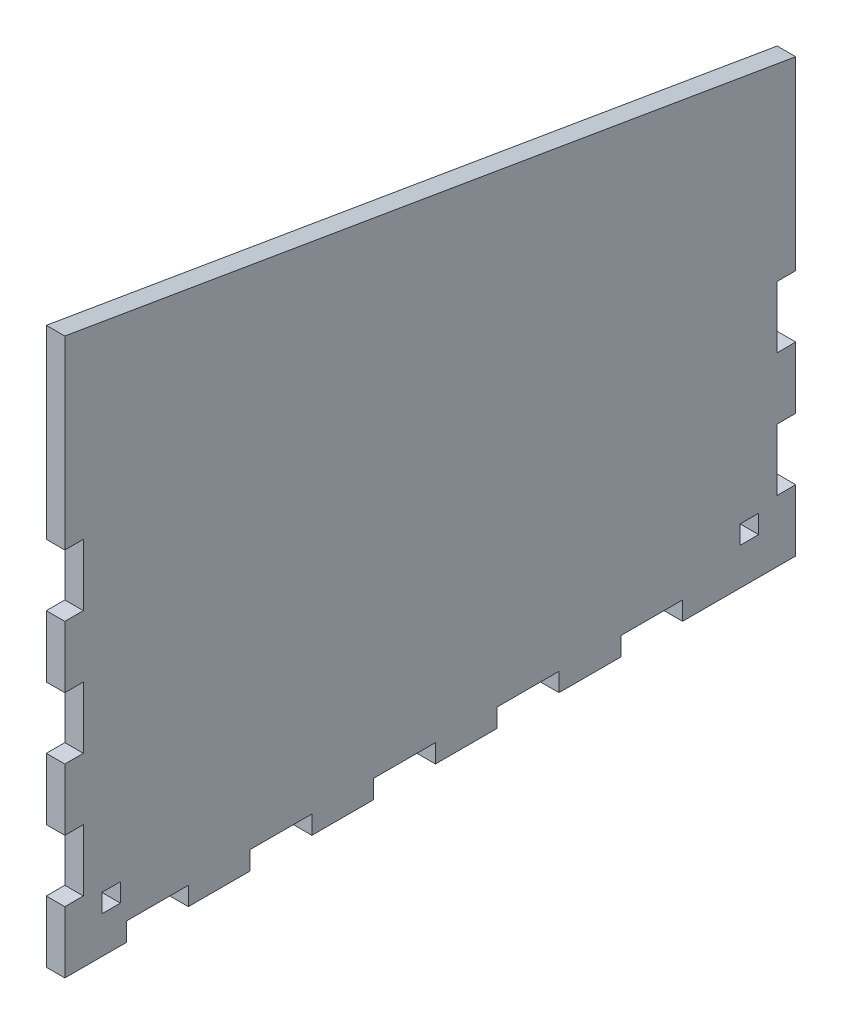
SolidWorks part; units mm, degrees
ref_plane "Front Plane" through (0, 0, 0) normal (0, 0, 1) x (1, 0, 0)
ref_plane "Top Plane" through (0, 0, 0) normal (0, 1, 0) x (1, 0, 0)
ref_plane "Right Plane" through (0, 0, 0) normal (1, 0, 0) x (0, 0, -1)
sketch "Sketch1" plane through (0, 0, 0) normal (1, 0, 0) x (0, 0, -1)
  line L0 (0, 0) -> (10, 0)
  line L1 (118.3216, 40) -> (118.3216, 70)
  line L2 (118.3216, 70) -> (0, 90)
  line L3 (0, 90) -> (0, 60)
  line L4 (118.3216, 40) -> (115.3216, 40)
  line L5 (115.3216, 40) -> (115.3216, 30)
  line L6 (115.3216, 30) -> (118.3216, 30)
  line L7 (118.3216, 30) -> (118.3216, 20)
  line L8 (118.3216, 20) -> (115.3216, 20)
  line L9 (115.3216, 20) -> (115.3216, 10)
  line L10 (115.3216, 10) -> (118.3216, 10)
  line L11 (118.3216, 10) -> (118.3216, 0)
  line L12 (0, 60) -> (3.0037, 60)
  line L13 (3.0037, 60) -> (3.0037, 50)
  line L14 (3.0037, 50) -> (0, 50)
  line L15 (0, 50) -> (0, 40)
  line L16 (0, 40) -> (3.0037, 40)
  line L17 (3.0037, 40) -> (3.0037, 30)
  line L18 (3.0037, 30) -> (0, 30)
  line L19 (0, 30) -> (0, 20)
  line L20 (0, 20) -> (3.0037, 20)
  line L21 (3.0037, 20) -> (3.0037, 10)
  line L22 (3.0037, 10) -> (0, 10)
  line L23 (0, 10) -> (0, 0)
  line L24 (10, 0) -> (10, 3)
  line L25 (10, 3) -> (20, 3)
  line L26 (20, 3) -> (20, 0)
  line L27 (20, 0) -> (30, 0)
  line L28 (30, 0) -> (30, 3)
  line L29 (30, 3) -> (40, 3)
  line L30 (40, 3) -> (40, 0)
  line L31 (40, 0) -> (50, 0)
  line L32 (50, 0) -> (50, 3)
  line L33 (50, 3) -> (60, 3)
  line L34 (60, 3) -> (60, 0)
  line L35 (60, 0) -> (70, 0)
  line L36 (70, 0) -> (70, 3)
  line L37 (70, 3) -> (80, 3)
  line L38 (80, 3) -> (80, 0)
  line L39 (80, 0) -> (90, 0)
  line L40 (90, 0) -> (90, 3)
  line L41 (90, 3) -> (100, 3)
  line L42 (100, 3) -> (100, 0)
  line L43 (100, 0) -> (118.3216, 0)
  line L44 (112.32, 6) -> (112.32, 9)
  line L45 (9, 6) -> (6, 6)
  line L46 (9, 6) -> (9, 9)
  line L47 (9, 9) -> (6, 9)
  line L48 (6, 6) -> (6, 9)
  line L49 (112.32, 9) -> (109.32, 9)
  line L50 (109.32, 6) -> (109.32, 9)
  line L51 (112.32, 6) -> (109.32, 6)
  dimension "D1" = 120
  dimension "D3" = 10
  dimension "D4" = 10
  dimension "D5" = 10
  dimension "D6" = 10
  dimension "D7" = 10
  dimension "D8" = 3
  dimension "D9" = 3
  dimension "D10" = 3
  dimension "D11" = 3.0037
  dimension "D12" = 10
  dimension "D13" = 3
  dimension "D14" = 10
  dimension "D15" = 10
  dimension "D16" = 10
  dimension "D17" = 10
  dimension "D18" = 10
  dimension "D19" = 10
  dimension "D20" = 10
  dimension "D21" = 10
  dimension "D22" = 10
  dimension "D23" = 3
  dimension "D24" = 3
  dimension "D25" = 6
  dimension "D26" = 6
  dimension "D27" = 2
  dimension "D28" = 70
extrude "Boss-Extrude1" add sketch "Sketch1" along normal blind 3
